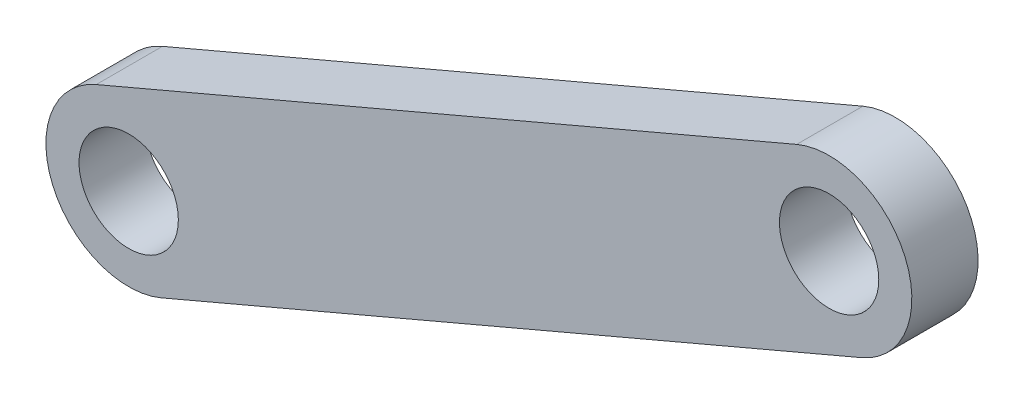
SolidWorks part; units mm, degrees
ref_plane "Plan de face" through (0, 0, 0) normal (0, 0, 1) x (1, 0, 0)
ref_plane "Plan de dessus" through (0, 0, 0) normal (0, 1, 0) x (1, 0, 0)
ref_plane "Plan de droite" through (0, 0, 0) normal (1, 0, 0) x (0, 0, -1)
sketch "Esquisse1" plane through (0, 0, 0) normal (0, 0, 1) x (1, 0, 0)
  line L0 (0, -5) -> (-21.1599, -14.0144) construction
  line L1 (0.9798, -7.3) -> (-20.18, -16.3144)
  line L2 (-0.9798, -2.7) -> (-22.1397, -11.7145)
  line L7 (-6.0595, -4.8641) -> (-22.1397, -11.7145)
  line L8 (-20.18, -16.3144) -> (0.9798, -7.3)
  arc A0 (0.9798, -7.3) -> (-0.9798, -2.7) centre (0, -5) ccw
  arc A1 (-22.1397, -11.7145) -> (-20.18, -16.3144) centre (-21.1599, -14.0144) ccw
  arc A4 (-0.3537, -2.5252) -> (0.9798, -7.3) centre (0, -5) cw
  arc A5 (-20.18, -16.3144) -> (-22.1397, -11.7145) centre (-21.1599, -14.0144) cw
  point P4 (-10.5799, -9.5072)
  point P17 (-6.0595, -4.8641)
  dimension "D1" = 5
extrude "Boss.-Extru.1" add sketch "Esquisse1" along normal blind 2 from offset 4 offset against normal yes
sketch "Esquisse2" plane through (0, 0, -2) normal (0, 0, 1) x (1, 0, 0)
  circle A0 centre (-21.1599, -14.0144) radius 1.5
  circle A1 centre (0, -5) radius 1.5
  dimension "D1" = 3
  dimension "D2" = 3
extrude "Enlèv. mat.-Extru.1" cut sketch "Esquisse2" against normal blind 2
